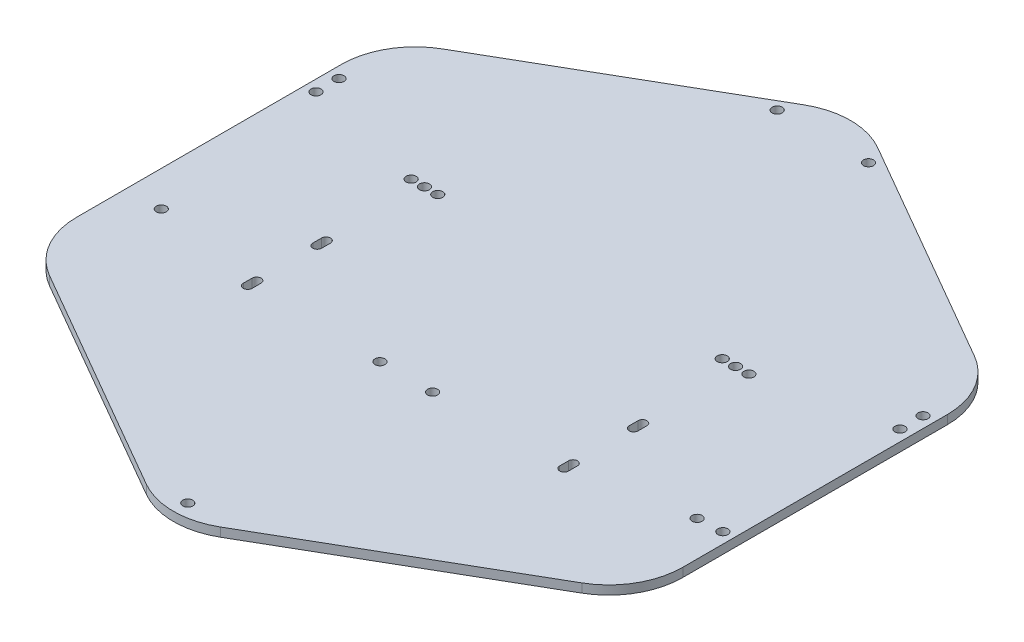
SolidWorks part; units mm, degrees
material "Alu"
ref_plane "Plan de face" through (0, 0, 0) normal (0, 0, 1) x (1, 0, 0)
ref_plane "Plan de dessus" through (0, 0, 0) normal (0, 1, 0) x (1, 0, 0)
ref_plane "Plan de droite" through (0, 0, 0) normal (1, 0, 0) x (0, 0, -1)
sketch "Esquisse1" plane through (0, 0, 0) normal (0, 1, 0) x (1, 0, 0)
  line L0 (-102.5, 0) -> (102.5, 0) construction
  line L1 (-102.5, 59.1784) -> (-102.5, -59.1784)
  line L2 (102.5, 59.1784) -> (102.5, -59.1784)
  line L3 (-102.5, -59.1784) -> (0, -118.3568)
  line L5 (0, -118.3568) -> (102.5, -59.1784)
  line L6 (102.5, 59.1784) -> (0, 118.3568)
  line L8 (0, 118.3568) -> (-102.5, 59.1784)
  line L9 (0, -118.3568) -> (0, 118.3568) construction
  line L10 (-102.5, 59.1784) -> (102.5, 59.1784) construction
  line L11 (102.5, -59.1784) -> (-102.5, -59.1784) construction
  circle A1 centre (0, 0) radius 102.5 construction
  point P13 (0, 0)
  dimension "D5" = 118.3568
  dimension "D1" = 205
  dimension "D6" = 118.3568
extrude "Boss.-Extru.1" add sketch "Esquisse1" along normal blind 3
fillet "Congé8" radius 25 6 edges at (102.5, 1.5, 59.1784) (-102.5, 1.5, 59.1784) (-102.5, 1.5, -59.1784) (102.5, 1.5, -59.1784) (0, 1.5, -118.3568) (0, 1.5, 118.3568)
hole_wizard "Dégagement M31" positions "Esquisse3" profile "Esquisse2" hole size "M3" standard "ISO" end condition through all
sketch "Esquisse3" plane through (0, 3, 0) normal (0, 1, 0) x (1, 0, 0)
  line L0 (0, 0) -> (0, 58.6143) construction
  point P9 (57.1, 23)
  point P12 (48.1, 23)
  point P15 (52.6, 23)
  point P22 (-52.6, 23)
  point P23 (-48.1, 23)
  point P24 (-57.1, 23)
  point P38 (-127.3191, 28.9106)
sketch "Esquisse2" plane through (57.1, 3, -23) normal (1, 0, 0) x (0, 0, 1)
  line L0 (0, 0) -> (0, 3)
  line L1 (0, 3) -> (1.7, 3)
  line L2 (1.7, 3) -> (1.7, 0)
  line L5 (1.7, 0) -> (0, 0)
  line L11 (0, -6.35) -> (0, 107.95) construction
  dimension "Diamètre du perçage jusqu'au prochain" = 3.4
  dimension "Profondeur du perçage jusqu'au prochain" = 3
sketch "Esquisse4" plane through (0, 3, 0) normal (0, 1, 0) x (1, 0, 0)
  line L0 (0, 0) -> (0, -47.7179) construction
  line L1 (-53.5, -9.3721) -> (-53.5, -12.3721) construction
  line L2 (-55, -9.3721) -> (-55, -12.3721)
  line L3 (-52, -9.3721) -> (-52, -12.3721)
  line L4 (-53.5, -32.8721) -> (-53.5, -35.8721) construction
  line L5 (-55, -32.8721) -> (-55, -35.8721)
  line L6 (53.5, -9.3721) -> (53.5, -12.3721) construction
  line L7 (55, -9.3721) -> (55, -12.3721)
  line L8 (52, -9.3721) -> (52, -12.3721)
  line L9 (53.5, -32.8721) -> (53.5, -35.8721) construction
  line L10 (55, -32.8721) -> (55, -35.8721)
  line L11 (52, -32.8721) -> (52, -35.8721)
  line L12 (-52, -32.8721) -> (-52, -35.8721)
  line L13 (48.5, -34.3721) -> (58.5, -34.3721) construction
  arc A0 (-55, -9.3721) -> (-52, -9.3721) centre (-53.5, -9.3721) cw
  arc A1 (-52, -12.3721) -> (-55, -12.3721) centre (-53.5, -12.3721) cw
  arc A2 (-55, -32.8721) -> (-52, -32.8721) centre (-53.5, -32.8721) cw
  arc A3 (-52, -35.8721) -> (-55, -35.8721) centre (-53.5, -35.8721) cw
  arc A4 (55, -9.3721) -> (52, -9.3721) centre (53.5, -9.3721) ccw
  arc A5 (52, -12.3721) -> (55, -12.3721) centre (53.5, -12.3721) ccw
  arc A6 (55, -32.8721) -> (52, -32.8721) centre (53.5, -32.8721) ccw
  arc A7 (52, -35.8721) -> (55, -35.8721) centre (53.5, -35.8721) ccw
  point P5 (-53.5, -10.8721)
  point P13 (-53.5, -34.3721)
  point P17 (53.5, -10.8721)
  point P25 (53.5, -34.3721)
  dimension "D1" = 3
  dimension "D2" = 3
extrude "Enlèv. mat.-Extru.1" cut sketch "Esquisse4" against normal through all
hole_wizard "Dégagement M35" positions "Esquisse16" profile "Esquisse15" hole size "M3" standard "ISO"
sketch "Esquisse16" plane through (0, 3, 0) normal (0, 1, 0) x (1, 0, 0)
  point P3 (-90.5945, -27.9945)
  point P6 (-8.9, -35.75)
  point P9 (8.9, -35.75)
  point P12 (0, -109.6393)
  point P15 (90.5945, -27.9945)
  point P18 (98.85, -27.55)
  point P21 (98.75, 32.45)
  point P24 (98.75, 40.25)
  point P27 (15.4381, 105.1135)
  point P30 (-15.4381, 105.1135)
  point P33 (-98.75, 32.45)
  point P36 (-98.75, 40.25)
sketch "Esquisse15" plane through (-90.5945, 3, 27.9945) normal (1, 0, 0) x (0, 0, 1)
  line L0 (0, 0) -> (0, 8.0215)
  line L1 (0, 8.0215) -> (1.7, 7)
  line L2 (1.7, 7) -> (1.7, 0)
  line L5 (1.7, 0) -> (0, 0)
  line L10 (0, 8.0215) -> (-1.7, 7) construction
  line L11 (0, -6.35) -> (0, 107.95) construction
  dimension "Diamètre du perçage" = 3.4
  dimension "Profondeur du perçage" = 7
  dimension "Angle de pointe" = 118
